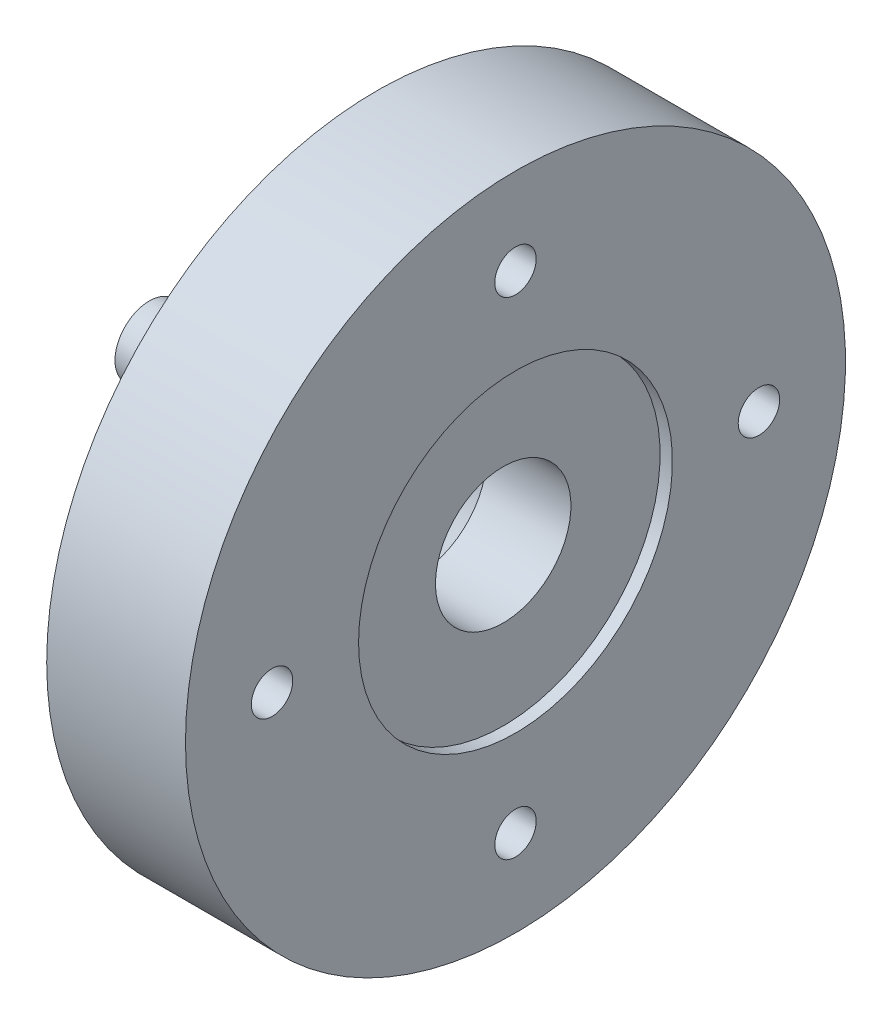
SolidWorks part; units mm, degrees
ref_plane "Front Plane" through (0, 0, 0) normal (0, 0, 1) x (1, 0, 0)
ref_plane "Top Plane" through (0, 0, 0) normal (0, 1, 0) x (1, 0, 0)
ref_plane "Right Plane" through (0, 0, 0) normal (1, 0, 0) x (0, 0, -1)
sketch "Sketch1" plane through (0, 0, 0) normal (0, 0, 1) x (1, 0, 0)
  line L0 (-795.1638, 11.7142) -> (36114.285, 11.7142) construction
  line L3 (-71.2919, 14.8842) -> (-71.2919, 14.5342)
  line L8 (-75.7419, 13.3992) -> (-59.4889, 13.3992)
  line L9 (-75.7419, 13.3992) -> (-75.7419, 14.5342)
  line L10 (-45.7058, 26.2025) -> (-45.7058, 38.788)
  line L12 (-45.7058, 38.788) -> (-57.0912, 38.788)
  line L13 (-62.3716, 14.5342) -> (-59.4889, 23.788)
  line L15 (-45.7058, 26.2025) -> (-45.7058, 24.5892)
  line L16 (-45.7058, 24.5892) -> (-46.7158, 24.5892)
  line L17 (-46.7158, 24.5892) -> (-46.7158, 17.2704)
  line L18 (-57.0912, 38.788) -> (-57.0912, 23.788)
  line L19 (-59.4889, 23.788) -> (-57.0912, 23.788)
  line L20 (-59.4889, 13.3992) -> (-53.6375, 17.2704)
  line L21 (-75.7419, 14.5342) -> (-71.2919, 14.8842)
  line L22 (-53.6375, 17.2704) -> (-46.7158, 17.2704)
  line L23 (-71.2919, 14.5342) -> (-66.8419, 14.8842)
  line L26 (-66.8419, 14.8842) -> (-66.8419, 14.5342)
  line L27 (-66.8419, 14.5342) -> (-62.3716, 14.8842)
  line L28 (-62.3716, 14.8842) -> (-62.3716, 14.5342)
  dimension "D1" = 25.75
  dimension "D5" = 11.1125
  dimension "D2" = 6.34
  dimension "D3" = 1.01
  dimension "D4" = 15
  dimension "D6" = 3.37
  dimension "D7" = 5.64
revolve "Revolve17" add sketch "Sketch1" angle 360 about L0
sketch "Sketch3" plane through (-57.0912, 0, 0) normal (-1, 0, 0) x (0, 0, 1)
  circle A2 centre (0, 11.7142) radius 19.9711 construction
  point P2 (0, 31.6853)
  point P3 (19.9711, 11.7142)
  point P4 (0, -8.2569)
  point P6 (-19.9711, 11.7142)
hole_wizard "CBORE for M3 Hex Socket Head Cap Screw1" positions "Sketch3" profile "Sketch4" counterbore size "M3" standard "ISO" end condition through all
sketch "Sketch4" plane through (-57.0912, 11.7142, -19.9711) normal (0, 1, 0) x (0, 0, 1)
  line L0 (0, 0) -> (0, 11.3854)
  line L1 (0, 11.3854) -> (1.7, 11.3854)
  line L3 (1.7, 11.3854) -> (1.7, 3.4)
  line L4 (3.25, 3.4) -> (1.7, 3.4)
  line L5 (3.25, 3.4) -> (3.25, 0.025)
  line L6 (3.25, 0.025) -> (3.275, 0)
  line L7 (3.275, 0) -> (0, 0)
  line L8 (-3.25, 0.025) -> (-3.275, 0) construction
  line L11 (0, -6.35) -> (0, 107.95) construction
  dimension "Thru Hole Dia." = 3.4
  dimension "Thru Hole Depth" = 11.3854
  dimension "C'Bore Dia." = 6.5
  dimension "C'Bore Depth" = 3.4
  dimension "Near C'Sink Dia." = 6.55
  dimension "Near C'Sink Angle" = 90
